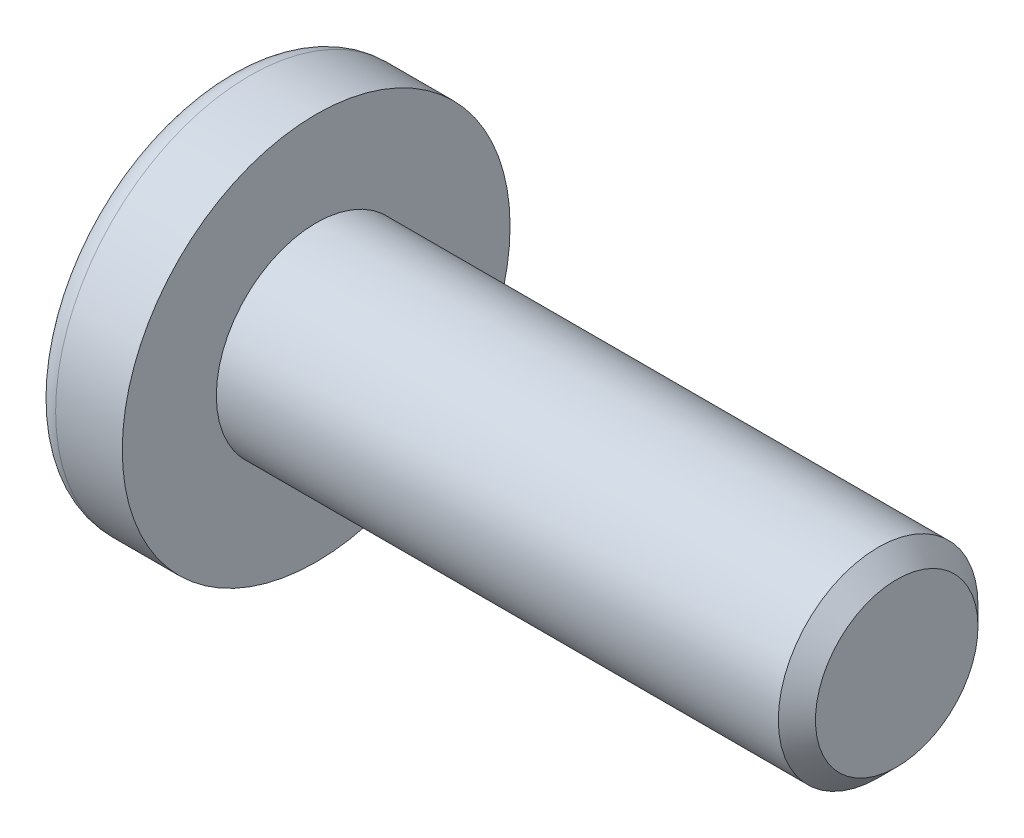
SolidWorks part; units mm, degrees
material "Alloy Steel"
ref_plane "Plane1" through (0, 0, 0) normal (0, 0, 1) x (1, 0, 0)
ref_plane "Plane2" through (0, 0, 0) normal (0, 1, 0) x (1, 0, 0)
ref_plane "Plane3" through (0, 0, 0) normal (1, 0, 0) x (0, 0, -1)
sketch "BodySke" plane through (0, 0, 0) normal (0, 0, 1) x (1, 0, 0)
  line L0 (1.5748, 1.0922) -> (1.5748, 2.1209)
  line L1 (1.8021, 6.35) -> (1.8021, -3.175) construction
  line L2 (-25.4, 0) -> (127, 0) construction
  line L3 (7.9248, 0) -> (0, 0)
  line L4 (1.5748, 1.0922) -> (7.9248, 1.0922)
  line L5 (7.9248, 1.0922) -> (7.9248, 0)
  line L6 (0.8457, 2.1209) -> (1.5748, 2.1209)
  line L7 (1.5748, -1.0922) -> (7.9248, -1.0922) construction
  line L8 (1.5748, 6.35) -> (1.5748, -3.175) construction
  arc A0 (0.6381, 2.0132) -> (0, 0) centre (3.495, 0) ccw
  arc A2 (0.6381, 2.0132) -> (0.8457, 2.1209) centre (0.8457, 1.8669) cw
  dimension "Head_crown_rad" = 3.495
  dimension "Head_fillet_rad" = 0.254
  dimension "Diameter" = 2.1844
  dimension "Length" = 6.35
  dimension "Head_ht" = 1.5748
  dimension "Head_dia" = 4.2418
  dimension "Advance" = 0.4547
  dimension "Thread_nom" = 6.35
revolve "Base-Revolve" add sketch "BodySke" angle 360 about L2
cosmetic thread "ThreadCosmetic" parameters "Thread_length"=5.8953, "Thread_minor"=1.6459
sketch "Sketch3" plane through (0, 0, 0) normal (1, 0, 0) x (0, 0, -1)
  line L0 (0.3429, -1.3843) -> (-0.3429, -1.3843)
  line L1 (0.3429, -1.3843) -> (0.3429, 1.3843)
  line L2 (-0.3429, 1.3843) -> (0.3429, 1.3843)
  line L3 (-0.3429, 1.3843) -> (-0.3429, -1.3843)
  dimension "Cross_dia" = 2.7686
  dimension "D1" = 1.3843
  dimension "Cross_width" = 0.6858
  dimension "D2" = 0.3429
ref_plane "Plane4" through (1.4986, 0, 0) normal (1, 0, 0) x (0, 0, -1)
sketch "Sketch4" plane through (1.4986, 0, 0) normal (1, 0, 0) x (0, 0, -1)
  line L0 (0.1714, -0.1715) -> (-0.1714, -0.1715)
  line L1 (0.1714, -0.1715) -> (0.1714, 0.1715)
  line L2 (-0.1714, 0.1714) -> (0.1714, 0.1715)
  line L3 (-0.1714, 0.1714) -> (-0.1714, -0.1715)
  dimension "D2" = 0.3429
  dimension "D1" = 0.3429
  dimension "D3" = 0.1714
  dimension "D4" = 0.1714
loft "Cut-Loft1" cut profiles "Sketch3", "Sketch4"
pattern_circular "CirPattern1" count 2 every 90 about axis through (0, 0, 0) along (1, 0, 0) of "Cut-Loft1"
chamfer "Chamfer1" distance 0.2032 angle 45 1 edges at (7.9248, 0, 1.0922)
equation "\"D1@Sketch3\" = \"Cross_dia@Sketch3\" / 2"
equation "\"D2@Sketch3\" = \"Cross_width@Sketch3\" / 2"
equation "\"D1@Sketch4\" = \"Cross_width@Sketch3\" *.5"
equation "\"D2@Sketch4\" = \"D1@Sketch4\""
equation "\"D3@Sketch4\" = \"D1@Sketch4\" / 2"
equation "\"D4@Sketch4\" = \"D2@Sketch4\" / 2"
equation "\"Thread_length@ThreadCosmetic\" = ((sgn( (\"Length@BodySke\" - \"Advance@BodySke\" ) - \"Thread_nom@BodySke\" )-1)*( (\"Length@BodySke\" - \"Advance@BodySke\" ) - \"Thread_nom@BodySke\" ))/-2+ \"Thread_nom@BodySke\""
